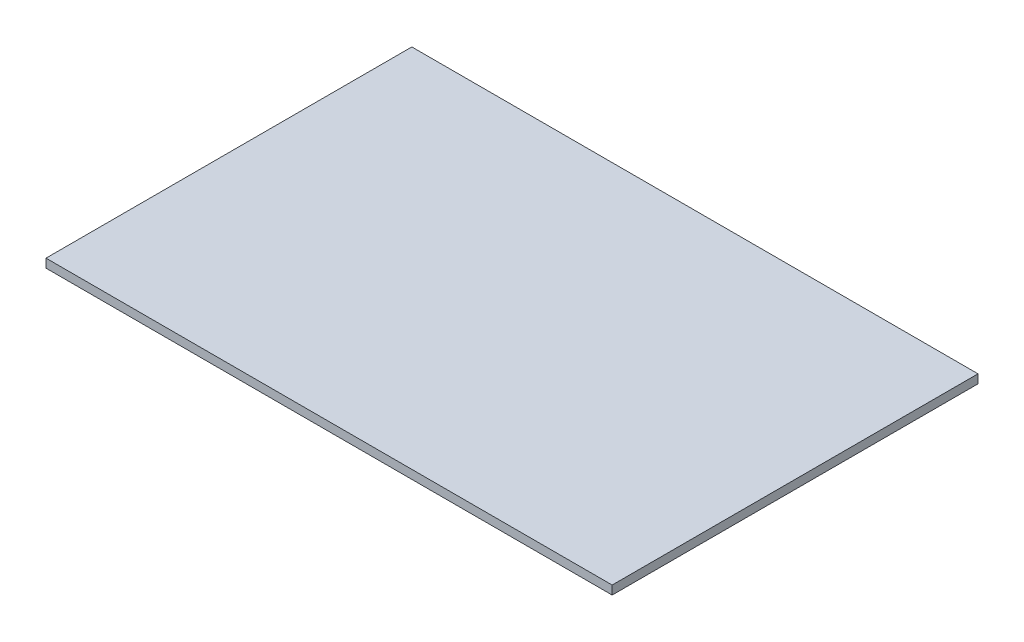
SolidWorks part; units mm, degrees
ref_plane "Alzado" through (0, 0, 0) normal (0, 0, 1) x (1, 0, 0)
ref_plane "Planta" through (0, 0, 0) normal (0, 1, 0) x (1, 0, 0)
ref_plane "Vista lateral" through (0, 0, 0) normal (1, 0, 0) x (0, 0, -1)
sketch "Croquis2" plane through (0, 0, 0) normal (0, 0, 1) x (1, 0, 0)
  line L1 (-97.5, 3) -> (97.5, 3)
  line L2 (-97.5, 3) -> (-97.5, 0)
  line L3 (-97.5, 0) -> (97.5, 0)
  line L4 (97.5, 3) -> (97.5, 0)
  point P4 (0, 0)
  dimension "D1" = 3
  dimension "D2" = 195
extrude "Saliente-Extruir2" add sketch "Croquis2" against normal blind 126
